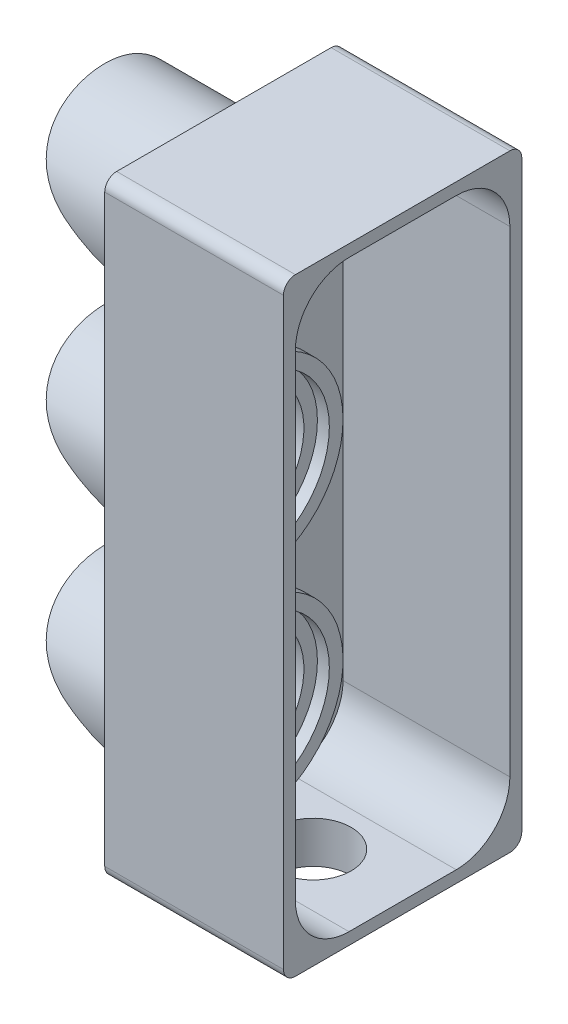
SolidWorks part; units mm, degrees
material "ABS PC"
ref_plane "Front Plane" through (0, 0, 0) normal (0, 0, 1) x (1, 0, 0)
ref_plane "Top Plane" through (0, 0, 0) normal (0, 1, 0) x (1, 0, 0)
ref_plane "Right Plane" through (0, 0, 0) normal (1, 0, 0) x (0, 0, -1)
sketch "Sketch1" plane through (0, 0, 0) normal (1, 0, 0) x (0, 0, -1)
  line L0 (0, 0) -> (0, 70) construction
  line L1 (0, 70) -> (0, 86) construction
  line L2 (-20, 86) -> (20, 86)
  line L3 (-20, 86) -> (-20, -16)
  line L4 (-20, -16) -> (20, -16)
  line L5 (20, 86) -> (20, -16)
  line L6 (0, -16) -> (0, 0) construction
  circle A0 centre (0, 70) radius 12.7
  circle A1 centre (0, 35) radius 12.7
  circle A2 centre (0, 0) radius 12.7
  dimension "D1" = 25.4
  dimension "D2" = 70
  dimension "D3" = 40
  dimension "D4" = 16
extrude "Boss-Extrude1" add sketch "Sketch1" along normal blind 30 contours L3 L4 L5 L2
shell "Shell1" thickness 2
sketch "Sketch2" plane through (0, 0, 0) normal (-1, 0, 0) x (0, 0, 1)
  circle A0 centre (0, 0) radius 11.43
  circle A1 centre (0, 35) radius 11.43
  circle A2 centre (0, 70) radius 11.43
  dimension "D1" = 22.86
extrude "Cut-Extrude1" cut sketch "Sketch2" against normal up to next
sketch "Sketch3" plane through (0, 0, 0) normal (-1, 0, 0) x (0, 0, 1)
  circle A0 centre (0, 0) radius 12.7 construction
  circle A1 centre (0, 35) radius 12.7 construction
  circle A2 centre (0, 70) radius 12.7 construction
  circle A3 centre (0, 0) radius 12.7
  circle A4 centre (0, 35) radius 12.7
  circle A5 centre (0, 70) radius 12.7
  circle A6 centre (0, 0) radius 11.43 construction
  circle A7 centre (0, 35) radius 11.43 construction
  circle A8 centre (0, 70) radius 11.43 construction
  circle A9 centre (0, 0) radius 11.43
  circle A10 centre (0, 35) radius 11.43
  circle A11 centre (0, 70) radius 11.43
extrude "Boss-Extrude2" add sketch "Sketch3" along normal blind 20
sketch "Sketch4" plane through (0, 0, 0) normal (0, 0, 1) x (1, 0, 0)
  line L3 (-20, 82.7) -> (-20, 57.3)
  line L4 (0, 57.3) -> (-13.8111, 69.3726)
  line L5 (0, 57.3) -> (-20, 57.3)
  line L6 (-20, 57.3) -> (-20, 81.43)
  arc A0 (-20, 82.7) -> (-13.8111, 69.3726) centre (-1.892, 83.0082) ccw
extrude "Cut-Extrude2" cut sketch "Sketch4" against normal up to next and the other way up to next contours A0 L3 L5 L4
pattern_linear "LPattern1" count 3 spacing 35 along (0, -1, 0) of "Cut-Extrude2"
sketch "Sketch5" plane through (2, 0, 0) normal (1, 0, 0) x (0, 0, -1)
  circle A0 centre (0, 70) radius 13.7
  circle A1 centre (0, 35) radius 13.7
  circle A2 centre (0, 0) radius 13.7
  circle A3 centre (0, 70) radius 12.7 construction
  circle A4 centre (0, 70) radius 16
  circle A5 centre (0, 35) radius 16
  circle A6 centre (0, 0) radius 16
  dimension "D1" = 1
extrude "Boss-Extrude3" add sketch "Sketch5" along normal blind 2
fillet "Fillet1" radius 2 4 edges at (15, -16, -20) (15, -16, 20) (15, 86, -20) (15, 86, 20)
sketch "Sketch6" plane through (0, -16, 0) normal (0, -1, 0) x (1, 0, 0)
  line L0 (0, 20) -> (30, 20) construction
  line L1 (30, -20) -> (0, -20) construction
  line L2 (0, 20) -> (30, 20) construction
  line L3 (30, -20) -> (0, -20) construction
  line L4 (0, -20) -> (30, 20) construction
  line L5 (0, -20) -> (30, -20) construction
  line L6 (0, -20) -> (0, 20) construction
  line L7 (0, 20) -> (30, 20) construction
  line L8 (30, -20) -> (30, 20) construction
  line L9 (30, -20) -> (0, 20) construction
  circle A0 centre (15, 0) radius 6.35
  dimension "D1" = 12.7
extrude "Cut-Extrude3" cut sketch "Sketch6" against normal up to next
sketch "Sketch7" plane through (0, -16, 0) normal (0, -1, 0) x (1, 0, 0)
  circle A0 centre (15, 0) radius 6.35 construction
  circle A1 centre (15, 0) radius 6.35
  circle A2 centre (15, 0) radius 7.35
  dimension "D1" = 1
extrude "Boss-Extrude4" add sketch "Sketch7" along normal blind 5
fillet "Fillet6" radius 9 4 edges at (16, -14, 18) (16, -14, -18) (16, 84, -18) (16, 84, 18)
